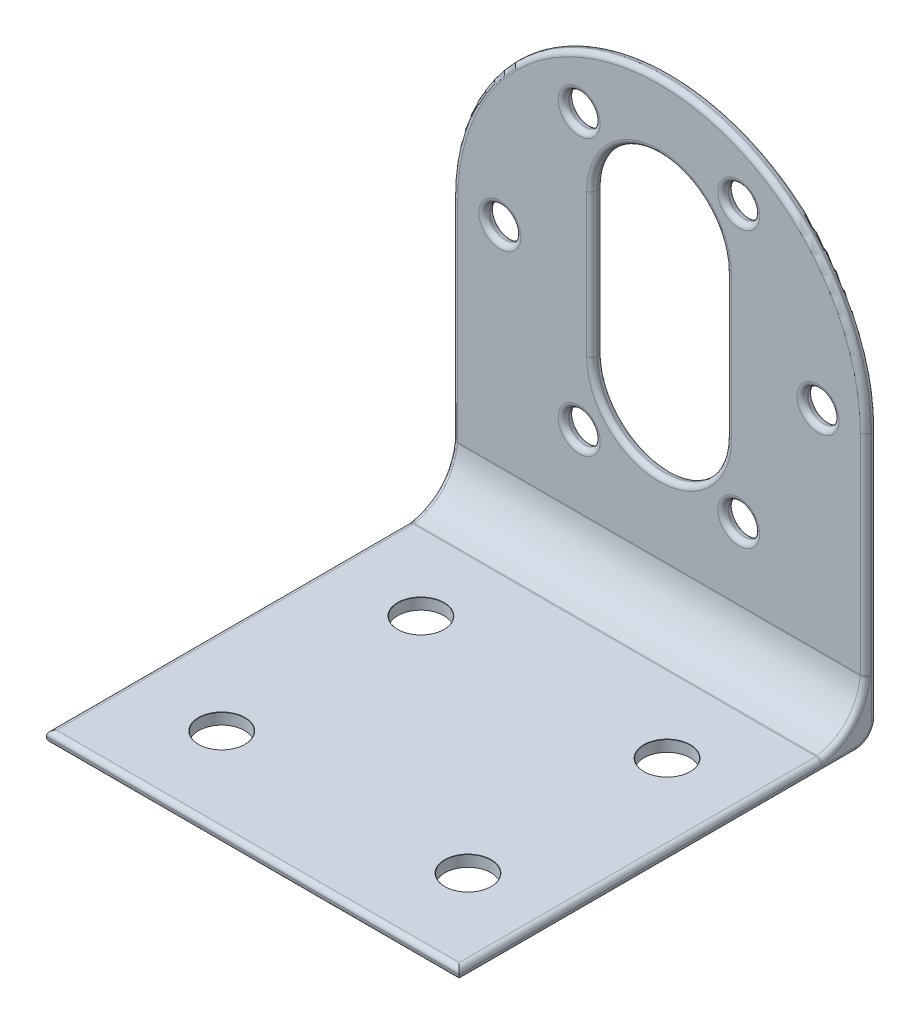
SolidWorks part; units mm, degrees
ref_plane "Front Plane" through (0, 0, 0) normal (0, 0, 1) x (1, 0, 0)
ref_plane "Top Plane" through (0, 0, 0) normal (0, 1, 0) x (1, 0, 0)
ref_plane "Right Plane" through (0, 0, 0) normal (1, 0, 0) x (0, 0, -1)
sketch "Sketch1" plane through (0, 0, 0) normal (0, 0, 1) x (1, 0, 0)
  line L4 (0.2424, 7.1284) -> (0.2424, 21.1084)
  line L10 (-26.5076, -12.3166) -> (13.8424, -12.3166)
  line L11 (13.8424, -12.3166) -> (13.8424, -2.8166)
  line L12 (13.8424, -2.8166) -> (13.8424, 14.0084)
  line L13 (-26.5076, 14.0084) -> (-26.5076, -2.8166)
  line L14 (-26.5076, -2.8166) -> (-26.5076, -12.3166)
  line L15 (-12.9076, 21.1084) -> (-12.9076, 7.1284)
  circle A2 centre (-14.1326, 27.4606) radius 1.55
  circle A4 centre (-21.8826, 14.0084) radius 1.55
  circle A6 centre (1.4674, 27.4606) radius 1.55
  circle A8 centre (9.2174, 14.0084) radius 1.55
  circle A10 centre (1.4674, 0.5562) radius 1.55
  circle A12 centre (-14.1326, 0.5562) radius 1.55
  arc A14 (13.8424, 14.0084) -> (-26.5076, 14.0084) centre (-6.3326, 14.0084) ccw
  arc A18 (-12.9076, 7.1284) -> (0.2424, 7.1284) centre (-6.3326, 7.1284) ccw
  arc A19 (0.2424, 21.1084) -> (-12.9076, 21.1084) centre (-6.3326, 21.1084) ccw
extrude "Boss-Extrude1" add sketch "Sketch1" along normal blind 1.1
sketch "Sketch2" plane through (0, 0, 1.1) normal (0, 0, 1) x (1, 0, 0)
  line L0 (13.8424, -12.3166) -> (13.8424, 14.0084) construction
  line L1 (-26.5076, -12.3166) -> (13.8424, -12.3166)
  line L2 (-26.5076, -12.3166) -> (-26.5076, -11.2166)
  line L3 (-26.5076, -11.2166) -> (13.8424, -11.2166)
  line L4 (13.8424, -12.3166) -> (13.8424, -11.2166)
  dimension "D1" = 1.1
extrude "Boss-Extrude2" add sketch "Sketch2" along normal blind 39.7
sketch "Sketch3" plane through (13.8424, 0, 0) normal (1, 0, 0) x (0, 0, -1)
  line L0 (-40.8, -11.2166) -> (-1.1, -11.2166) construction
  line L1 (0, -12.3166) -> (-5.3679, -12.3166)
  line L2 (0, -12.3166) -> (0, -6.5051)
  line L3 (0, -6.5051) -> (-1.1, -6.5051)
  line L4 (-5.3679, -12.3166) -> (-5.3679, -11.2166)
  line L5 (-1.1, -11.2166) -> (-1.1, 14.0084) construction
  spline S0 degree 2 poles (-1.1, -6.5051) (-1.5995, -10.4191) (-5.3679, -11.2166) knots 0 0 0 1 1 1
extrude "Boss-Extrude3" add sketch "Sketch3" against normal up to surface (40.35 mm away) up to face at (-26.5076, -3.1749, 13.9667)
fillet "Fillet1" radius 2 1 edges at (-6.3326, -12.3166, 0)
fillet "Fillet2" radius 0.5 38 edges at (13.8424, -11.7308, 0.5858) (-26.5076, -11.7308, 0.5858) (-6.3326, 0.5534, 1.1) (0.2424, 14.1184, 1.1) (-6.3326, 27.6834, 1.1) (-12.9076, 14.1184, 1.1) (-12.5826, 0.5562, 1.1) (10.7674, 14.0084, 1.1) (-20.3326, 14.0084, 1.1) (-12.5826, 27.4606, 1.1) (3.0174, 27.4606, 1.1) (3.0174, 0.5562, 1.1) (-26.5076, 3.7516, 1.1) (-6.3326, 34.1834, 1.1) (13.8424, 3.7516, 1.1) (-6.3326, -6.5051, 1.1) (0.2424, 14.1184, 0) (-6.3326, 0.5534, 0) (-12.9076, 14.1184, 0) (-6.3326, 27.6834, 0) (-6.3326, 34.1834, 0) (-26.5076, 1.8459, 0) (13.8424, 1.8459, 0) (-12.5826, 27.4606, 0) (-20.3326, 14.0084, 0) (3.0174, 27.4606, 0) (10.7674, 14.0084, 0) (3.0174, 0.5562, 0) (-12.5826, 0.5562, 0) (-6.3326, -12.3166, 40.8) (13.8424, -12.3166, 21.4) (-26.5076, -12.3166, 21.4) (-6.3326, -11.2166, 40.8) (-26.5076, -11.2166, 23.084) (-6.3326, -11.2166, 5.3679) (13.8424, -11.2166, 23.084)
hole_wizard "M4 Clearance Hole1" positions "3DSketch1" profile "Sketch5" hole size "M4" standard "ANSI Metric" end condition through all
sketch3d "3DSketch1"
  line L0 (-17.8626, -11.2166, 14.0881) -> (-17.8626, -11.2166, 20.5113) construction
  line L2 (-12.8626, -11.2166, 12.84) -> (7.1634, -11.2166, 12.84) construction
  line L4 (11.1974, -11.2166, 11.7601) -> (11.1974, -11.2166, 25.6889) construction
  line L8 (-17.8626, -11.2166, 12.84) -> (6.1974, -11.2166, 12.84)
  line L10 (-26.0076, -11.2166, 5.4211) -> (-26.0076, -11.2166, 40.3) construction
  point P0 (-17.8626, -11.2166, 12.84)
  point P2 (6.1974, -11.2166, 12.84)
  point P4 (6.1974, -11.2166, 32.2998)
  point P6 (-17.8626, -11.2166, 32.2998)
  point P40 (-5.8326, -11.2166, 12.84)
  dimension "D1" = 24.06
  dimension "D2" = 19.4598
  dimension "D3" = 24.06
  dimension "D4" = 20.175
  dimension "D5" = 12.84
sketch "Sketch5" plane through (-17.8626, -11.2166, 12.84) normal (1, 0, 0) x (0, 0, 1)
  line L0 (0, 0) -> (0, 1.1)
  line L1 (0, 1.1) -> (2.25, 1.1)
  line L2 (2.25, 1.1) -> (2.25, 0.025)
  line L3 (2.25, 0.025) -> (2.275, 0)
  line L5 (2.275, 0) -> (0, 0)
  line L6 (-2.25, 0.025) -> (-2.275, 0) construction
  line L11 (0, -6.35) -> (0, 107.95) construction
  dimension "Thru Hole Dia." = 4.5
  dimension "Thru Hole Depth" = 1.1
  dimension "Near C'Sink Dia." = 4.55
  dimension "Near C'Sink Angle" = 90
